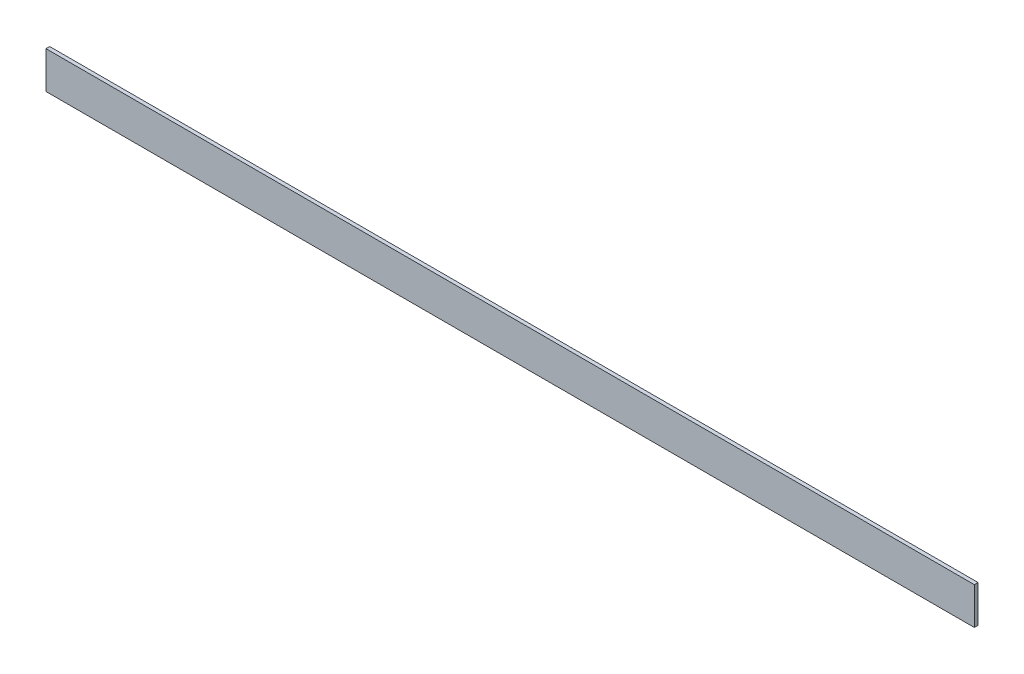
SolidWorks part; units mm, degrees
ref_plane "Front Plane" through (0, 0, 0) normal (0, 0, 1) x (1, 0, 0)
ref_plane "Top Plane" through (0, 0, 0) normal (0, 1, 0) x (1, 0, 0)
ref_plane "Right Plane" through (0, 0, 0) normal (1, 0, 0) x (0, 0, -1)
sketch "Sketch1" plane through (0, 0, 0) normal (0, 0, 1) x (1, 0, 0)
  line L1 (0, 0) -> (125, 0)
  line L2 (0, 0) -> (0, 5)
  line L3 (0, 5) -> (125, 5)
  line L4 (125, 0) -> (125, 5)
  dimension "D1" = 125
  dimension "D2" = 5
extrude "Profile" add sketch "Sketch1" along normal blind 0.5
equation "\"Profile_Depth\"= 0.5mm"
equation "\"D1@Profile\" = \"Profile_Depth\""
equation "\"Profile_Sketch_1\"= 125mm"
equation "\"D1@Sketch1\" = \"Profile_Sketch_1\""
equation "\"Profile_Sketch_2\"= 5mm"
equation "\"D2@Sketch1\" = \"Profile_Sketch_2\""
equation "\"EnvelopeWidth\"= 125mm"
equation "\"EnvelopeHeight\"= 5mm"
